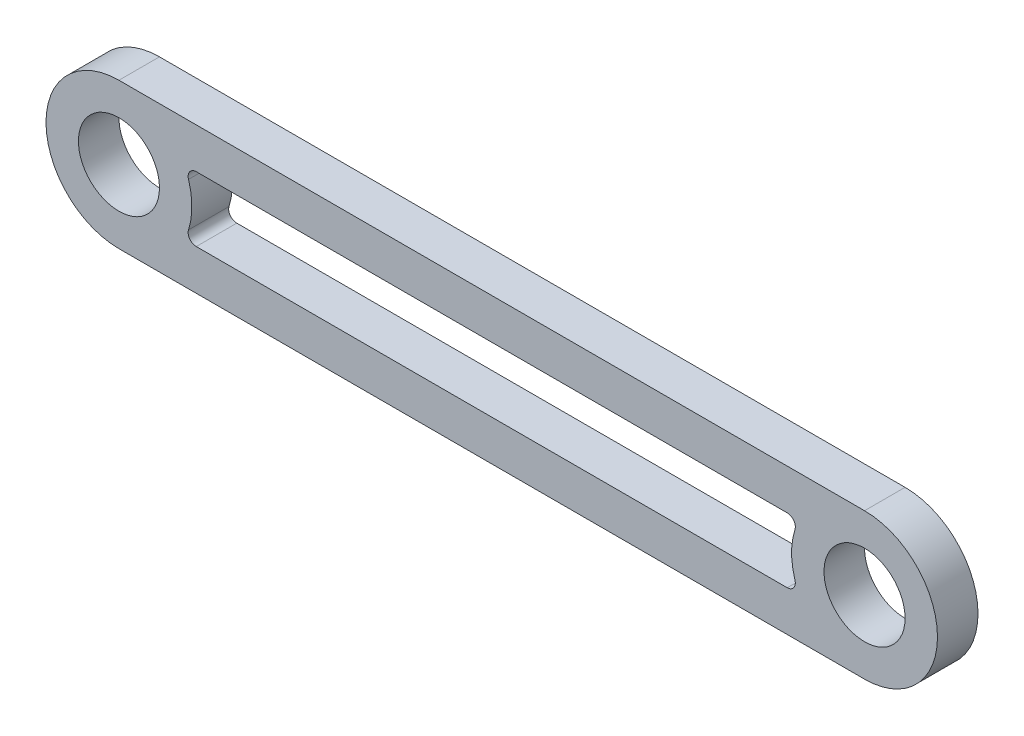
SolidWorks part; units mm, degrees
material "Thornel Mat VMA"
ref_plane "前视基准面" through (0, 0, 0) normal (0, 0, 1) x (1, 0, 0)
ref_plane "上视基准面" through (0, 0, 0) normal (0, 1, 0) x (1, 0, 0)
ref_plane "右视基准面" through (0, 0, 0) normal (1, 0, 0) x (0, 0, -1)
sketch "草图1" plane through (0, 0, 0) normal (0, 0, 1) x (1, 0, 0)
  line L0 (0, 0) -> (92, 0) construction
  line L1 (0, 9) -> (92, 9)
  line L2 (0, -9) -> (92, -9)
  arc A0 (0, 9) -> (0, -9) centre (0, 0) ccw
  arc A1 (92, -9) -> (92, 9) centre (92, 0) ccw
  circle A2 centre (0, 0) radius 5
  circle A3 centre (92, 0) radius 5
  point P3 (46, 0)
  dimension "D1" = 10
  dimension "D2" = 10
  dimension "D3" = 92
  dimension "D4" = 18
extrude "凸台-拉伸1" add sketch "草图1" along normal blind 5
sketch "草图2" plane through (0, 0, 5) normal (0, 0, 1) x (1, 0, 0)
  line L0 (9.5394, 4) -> (82.4606, 4)
  line L1 (92, 9) -> (0, 9) construction
  line L2 (0, 0) -> (-13.8848, 0) construction
  line L3 (9.5394, -4) -> (82.4606, -4)
  arc A0 (8.5855, -2.7) -> (8.5855, 2.7) centre (0, 0) ccw
  arc A1 (83.4145, 2.7) -> (83.4145, -2.7) centre (92, 0) ccw
  arc A2 (82.4606, 4) -> (83.4145, 2.7) centre (82.4606, 3) cw
  arc A3 (82.4606, -4) -> (83.4145, -2.7) centre (82.4606, -3) ccw
  arc A4 (9.5394, -4) -> (8.5855, -2.7) centre (9.5394, -3) cw
  arc A5 (9.5394, 4) -> (8.5855, 2.7) centre (9.5394, 3) ccw
  point P13 (83.9377, 4)
  point P16 (83.9377, -4)
  point P19 (8.0623, -4)
  point P22 (8.0623, 4)
  dimension "D1" = 18
  dimension "D2" = 18
  dimension "D4" = 1
  dimension "D3" = 5
extrude "切除-拉伸1" cut sketch "草图2" against normal through all
